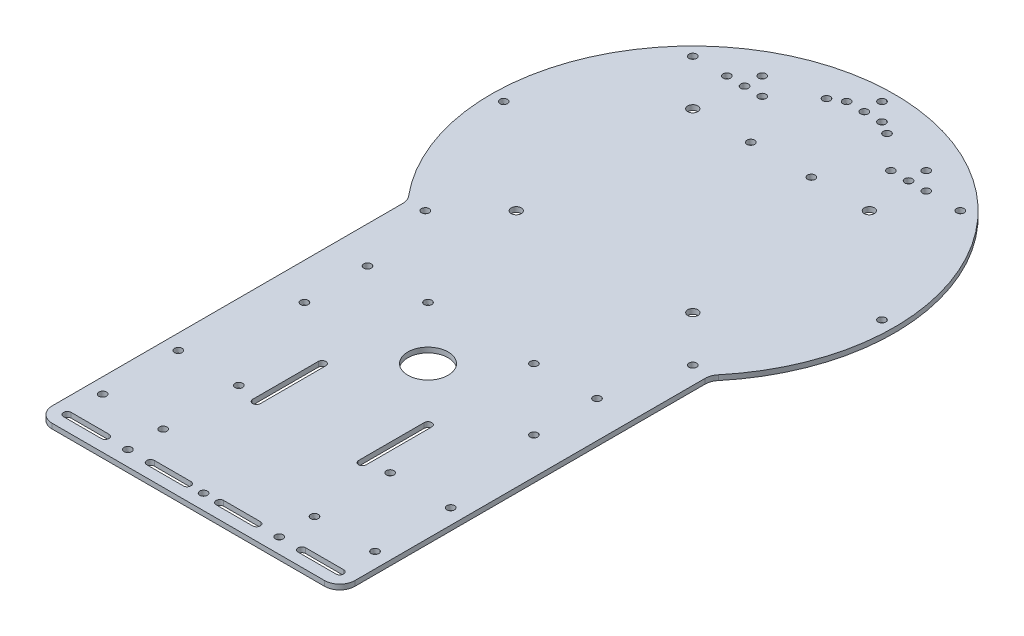
SolidWorks part; units mm, degrees
material "普通碳钢"
ref_plane "前视" through (0, 0, 0) normal (0, 0, 1) x (1, 0, 0)
ref_plane "上视" through (0, 0, 0) normal (0, 1, 0) x (1, 0, 0)
ref_plane "右视" through (0, 0, 0) normal (1, 0, 0) x (0, 0, -1)
sketch "草图1" plane through (0, 0, 0) normal (0, 1, 0) x (1, 0, 0)
  line L0 (394.7344, 186.438) -> (394.7344, 47.5742)
  line L1 (388.7344, 41.5742) -> (280.7344, 41.5742)
  line L2 (274.7344, 47.5742) -> (274.7344, 186.438)
  line L3 (354.2344, 115.5742) -> (354.2344, 89.5742)
  line L4 (357.2344, 89.5742) -> (357.2344, 115.5742)
  line L5 (312.2344, 115.5742) -> (312.2344, 89.5742)
  line L6 (315.2344, 89.5742) -> (315.2344, 115.5742)
  line L7 (373.7344, 46.0742) -> (388.7344, 46.0742)
  line L8 (388.7344, 49.0742) -> (373.7344, 49.0742)
  line L9 (295.7344, 49.0742) -> (280.7344, 49.0742)
  line L10 (280.7344, 46.0742) -> (295.7344, 46.0742)
  line L11 (341.2344, 46.0742) -> (355.7344, 46.0742)
  line L12 (355.7344, 49.0742) -> (341.2344, 49.0742)
  line L13 (328.2344, 49.0742) -> (313.7344, 49.0742)
  line L14 (313.7344, 46.0742) -> (328.2344, 46.0742)
  arc A0 (396.1297, 190.2847) -> (394.7344, 186.438) centre (400.7344, 186.438) ccw
  arc A1 (388.7344, 41.5742) -> (394.7344, 47.5742) centre (388.7344, 47.5742) ccw
  arc A2 (274.7344, 47.5742) -> (280.7344, 41.5742) centre (280.7344, 47.5742) ccw
  arc A3 (274.7344, 186.438) -> (273.339, 190.2847) centre (268.7344, 186.438) ccw
  arc A4 (396.1297, 190.2847) -> (273.339, 190.2847) centre (334.7344, 241.5742) ccw
  circle A5 centre (369.7362, 276.576) radius 2
  circle A6 centre (369.7362, 206.5724) radius 2
  circle A7 centre (299.7326, 206.5724) radius 2
  circle A8 centre (313.7344, 157.5742) radius 1.5
  circle A9 centre (355.7344, 157.5742) radius 1.5
  circle A10 centre (380.2344, 133.0742) radius 1.5
  circle A11 centre (380.2344, 158.0742) radius 1.5
  circle A12 centre (364.7344, 61.5742) radius 1.5
  circle A13 centre (388.7344, 61.5742) radius 1.5
  circle A14 centre (364.7344, 91.5742) radius 1.5
  circle A15 centre (388.7344, 91.5742) radius 1.5
  circle A16 centre (304.7344, 61.5742) radius 1.5
  circle A17 centre (280.7344, 61.5742) radius 1.5
  circle A18 centre (304.7344, 91.5742) radius 1.5
  circle A19 centre (280.7344, 91.5742) radius 1.5
  circle A20 centre (334.7344, 316.5742) radius 1.5
  circle A21 centre (281.7014, 294.6072) radius 1.5
  circle A22 centre (259.7344, 241.5742) radius 1.5
  circle A23 centre (281.7014, 188.5412) radius 1.5
  circle A24 centre (387.7674, 188.5412) radius 1.5
  circle A25 centre (409.7344, 241.5742) radius 1.5
  circle A26 centre (387.7674, 294.6072) radius 1.5
  circle A27 centre (322.7344, 306.576) radius 1.5
  circle A28 centre (346.7344, 306.576) radius 1.5
  circle A29 centre (322.7344, 276.576) radius 1.5
  circle A30 centre (346.7344, 276.576) radius 1.5
  circle A31 centre (334.7344, 309.5742) radius 1.5
  circle A32 centre (341.7344, 309.5742) radius 1.5
  circle A33 centre (327.7344, 309.5742) radius 1.5
  circle A34 centre (302.2179, 301.6072) radius 1.5
  circle A35 centre (302.2179, 294.6072) radius 1.5
  circle A36 centre (309.2179, 294.6072) radius 1.5
  circle A37 centre (295.2179, 294.6072) radius 1.5
  circle A38 centre (367.2509, 301.6072) radius 1.5
  circle A39 centre (367.2509, 294.6072) radius 1.5
  circle A40 centre (360.2509, 294.6072) radius 1.5
  circle A41 centre (374.2509, 294.6072) radius 1.5
  circle A42 centre (289.2344, 133.0742) radius 1.5
  circle A43 centre (289.2344, 158.0742) radius 1.5
  circle A44 centre (304.7344, 47.5742) radius 1.5
  circle A45 centre (364.7344, 47.5742) radius 1.5
  circle A46 centre (334.7344, 47.5742) radius 1.5
  circle A47 centre (334.7344, 136.5742) radius 8
  circle A48 centre (299.7326, 276.576) radius 2
  arc A49 (357.2344, 115.5742) -> (354.2344, 115.5742) centre (355.7344, 115.5742) ccw
  arc A50 (354.2344, 89.5742) -> (357.2344, 89.5742) centre (355.7344, 89.5742) ccw
  arc A51 (312.2344, 89.5742) -> (315.2344, 89.5742) centre (313.7344, 89.5742) ccw
  arc A52 (315.2344, 115.5742) -> (312.2344, 115.5742) centre (313.7344, 115.5742) ccw
  arc A53 (388.7344, 46.0742) -> (388.7344, 49.0742) centre (388.7344, 47.5742) ccw
  arc A54 (373.7344, 49.0742) -> (373.7344, 46.0742) centre (373.7344, 47.5742) ccw
  arc A55 (280.7344, 49.0742) -> (280.7344, 46.0742) centre (280.7344, 47.5742) ccw
  arc A56 (295.7344, 46.0742) -> (295.7344, 49.0742) centre (295.7344, 47.5742) ccw
  arc A57 (355.7344, 46.0742) -> (355.7344, 49.0742) centre (355.7344, 47.5742) ccw
  arc A58 (341.2344, 49.0742) -> (341.2344, 46.0742) centre (341.2344, 47.5742) ccw
  arc A59 (313.7344, 49.0742) -> (313.7344, 46.0742) centre (313.7344, 47.5742) ccw
  arc A60 (328.2344, 46.0742) -> (328.2344, 49.0742) centre (328.2344, 47.5742) ccw
  dimension "D1" = 3
extrude "凸台-拉伸1" add sketch "草图1" along normal blind 2
